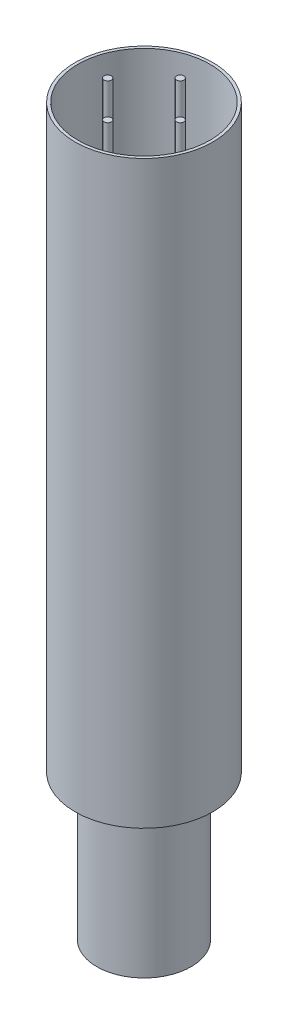
SolidWorks part; units mm, degrees
ref_plane "Front Plane" through (0, 0, 0) normal (0, 0, 1) x (1, 0, 0)
ref_plane "Top Plane" through (0, 0, 0) normal (0, 1, 0) x (1, 0, 0)
ref_plane "Right Plane" through (0, 0, 0) normal (1, 0, 0) x (0, 0, -1)
sketch "Sketch1" plane through (0, 0, 0) normal (0, 1, 0) x (1, 0, 0)
  circle A0 centre (0, 0) radius 32.5
  dimension "D1" = 65
extrude "Boss-Extrude1" add sketch "Sketch1" along normal blind 100
sketch "Sketch2" plane through (0, 100, 0) normal (0, 1, 0) x (1, 0, 0)
  circle A0 centre (0, 0) radius 47.5
  dimension "D1" = 95
extrude "Boss-Extrude2" add sketch "Sketch2" along normal blind 400
shell "Shell1" thickness 2
sketch "Sketch3" plane through (0, 102, 0) normal (0, 1, 0) x (1, 0, 0)
  circle A0 centre (-25, 0) radius 2.5
  circle A7 centre (0, 25) radius 2.5
  circle A8 centre (25, 0) radius 2.5
  circle A9 centre (0, -25) radius 2.5
  point P12 (0, 0)
  dimension "D1" = 5
  dimension "D2" = 25
  dimension "D3" = 4
extrude "Boss-Extrude3" add sketch "Sketch3" along normal blind 400
